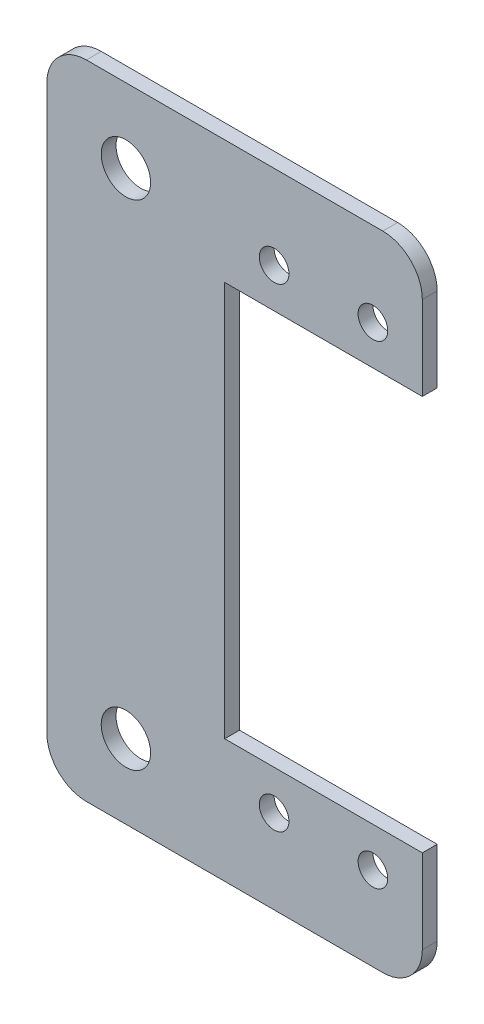
SolidWorks part; units mm, degrees
material "3.0205 (EN-AW 1200)"
ref_plane "Plan de face" through (0, 0, 0) normal (0, 0, 1) x (1, 0, 0)
ref_plane "Plan de dessus" through (0, 0, 0) normal (0, 1, 0) x (1, 0, 0)
ref_plane "Plan de droite" through (0, 0, 0) normal (1, 0, 0) x (0, 0, -1)
sketch "Esquisse1" plane through (0, 0, 0) normal (0, 0, 1) x (1, 0, 0)
  line L0 (38, -20) -> (38, -32.5)
  line L1 (38, 20) -> (18, 20)
  line L2 (28, 20) -> (28, -20) construction
  line L3 (38, -20) -> (18, -20)
  line L4 (18, 20) -> (18, -20)
  line L5 (38, 32.5) -> (0, 32.5)
  line L6 (38, 32.5) -> (38, 20)
  line L7 (38, -32.5) -> (0, -32.5)
  line L8 (0, 32.5) -> (0, -32.5)
  line L9 (0, 0) -> (28, 0) construction
  circle A0 centre (8, 25) radius 2.5
  circle A1 centre (23, 24) radius 1.5
  circle A2 centre (33, 24) radius 1.5
  circle A3 centre (33, -24) radius 1.5
  circle A4 centre (23, -24) radius 1.5
  circle A5 centre (8, -25) radius 2.5
  dimension "D1" = 10
  dimension "D2" = 3
  dimension "D3" = 48
  dimension "D6" = 10
  dimension "D7" = 8
  dimension "D8" = 7.5
  dimension "D10" = 5
  dimension "D4" = 40
  dimension "D5" = 20
  dimension "D9" = 12.5
extrude "Boss.-Extru.1" add sketch "Esquisse1" along normal blind 1.5
fillet "Congé1" radius 4 4 edges at (0, -32.5, 0.75) (38, -32.5, 0.75) (0, 32.5, 0.75) (38, 32.5, 0.75)
sketch "Esquisse2" plane through (0, 0, 1.5) normal (0, 0, 1) x (1, 0, 0)
  line L0 (0, 21.617) -> (5.2683, 20.2054)
  line L1 (0, 28.5) -> (0, -28.5) construction
  line L2 (5.2683, 20.2054) -> (0, 0.5437)
  line L3 (0, 0.5437) -> (0, 21.617)
  line L4 (-23.2265, 27.8405) -> (5.2683, 20.2054) construction
  line L5 (5.2683, 20.2054) -> (-11.8137, -43.5457) construction
extrude "Enlèv. mat.-Extru.1" [suppressed] cut sketch "Esquisse2" against normal through all
